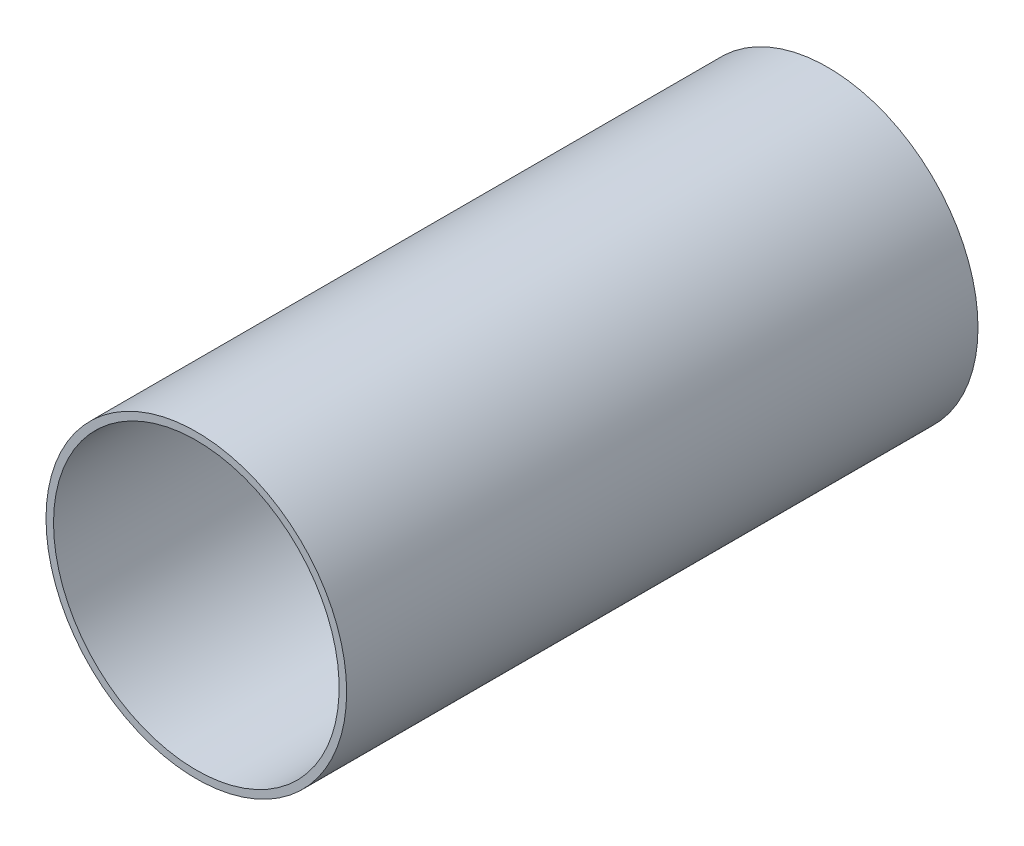
SolidWorks part; units mm, degrees
material "Acrylic (Medium-high impact)"
ref_plane "Front Plane" through (0, 0, 0) normal (0, 0, 1) x (1, 0, 0)
ref_plane "Top Plane" through (0, 0, 0) normal (0, 1, 0) x (1, 0, 0)
ref_plane "Right Plane" through (0, 0, 0) normal (1, 0, 0) x (0, 0, -1)
sketch "Sketch1" plane through (0, 0, 0) normal (1, 0, 0) x (0, 0, -1)
  line L0 (0, 63.5) -> (0, -63.5) construction
  line L1 (0, 0) -> (-92.9805, 0) construction
  line L2 (133.35, 63.5) -> (-133.35, 63.5)
  line L3 (-133.35, 63.5) -> (-133.35, 60.325)
  line L4 (-133.35, 60.325) -> (-0.5077, 60.325)
  line L8 (133.35, 60.325) -> (-0.5077, 60.325)
  line L9 (133.35, 63.5) -> (133.35, 60.325)
  point P3 (0, 0)
  point P12 (0, 51.1668)
  dimension "D1" = 127
  dimension "D2" = 266.7
  dimension "D3" = 3.175
revolve "Revolve1" add sketch "Sketch1" angle 360 about L1
